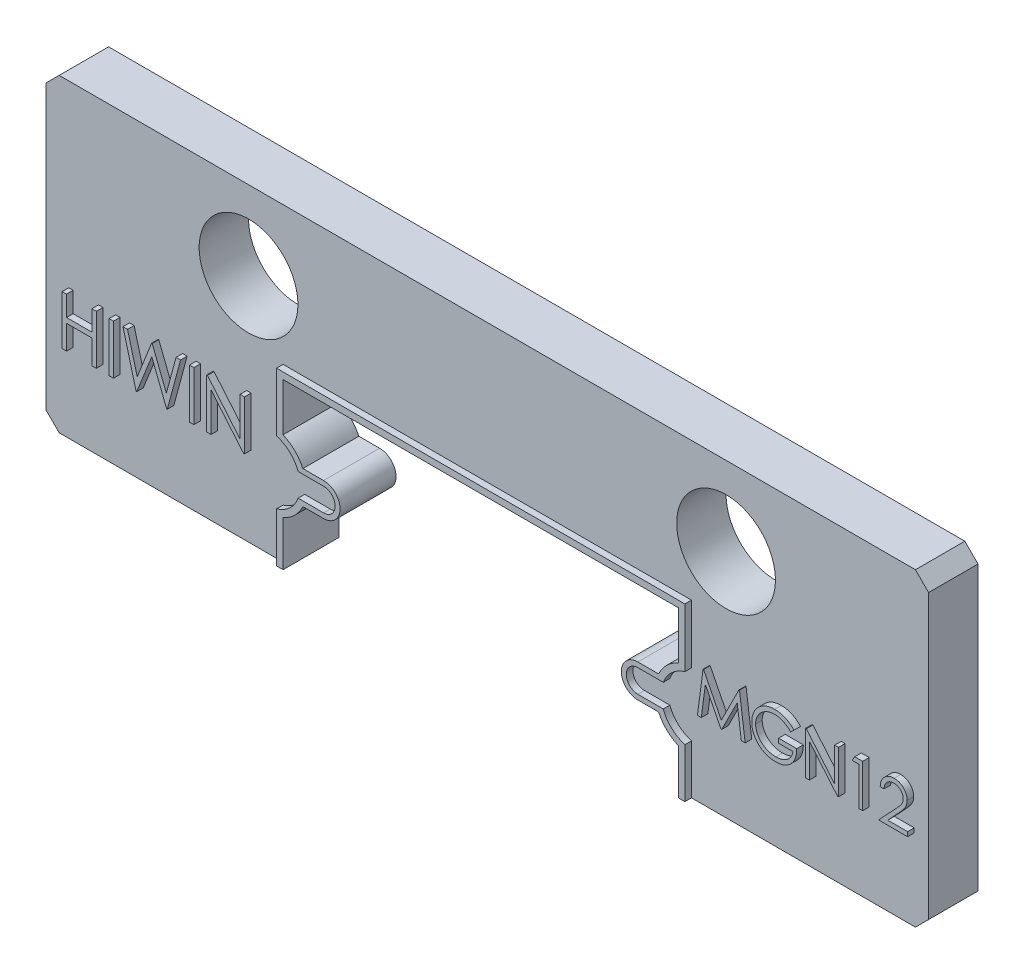
SolidWorks part; units mm, degrees
material "EPDM 60 Durometer"
ref_plane "Front Plane" through (0, 0, 0) normal (0, 0, 1) x (1, 0, 0)
ref_plane "Top Plane" through (0, 0, 0) normal (0, 1, 0) x (1, 0, 0)
ref_plane "Right Plane" through (0, 0, 0) normal (1, 0, 0) x (0, 0, -1)
sketch "Sketch1" plane through (0, 0, 0) normal (0, 0, 1) x (1, 0, 0)
  line L0 (0, 4.7) -> (0, -4.7) construction
  line L19 (-6, -4.7) -> (-13, -4.7)
  line L20 (-13, -4.7) -> (-13.4, -4.3)
  line L21 (-13.4, -4.3) -> (-13.4, 4.3)
  line L22 (-13.4, 4.3) -> (-13, 4.7)
  line L24 (-6, -4.7) -> (-6, -3.3289)
  line L25 (-6, -1.1511) -> (-6, 0.3)
  line L33 (-4.77, -2.74) -> (-5.4001, -2.74)
  line L34 (-4.77, -1.74) -> (-5.4001, -1.74)
  line L35 (-13, 4.7) -> (13, 4.7)
  line L36 (-6, 0.3) -> (6, 0.3)
  line L37 (6, -1.1511) -> (6, 0.3)
  line L38 (4.77, -1.74) -> (5.4001, -1.74)
  line L39 (4.77, -2.74) -> (5.4001, -2.74)
  line L40 (6, -4.7) -> (6, -3.3289)
  line L41 (6, -4.7) -> (13, -4.7)
  line L42 (13, -4.7) -> (13.4, -4.3)
  line L43 (13.4, -4.3) -> (13.4, 4.3)
  line L44 (13.4, 4.3) -> (13, 4.7)
  circle A6 centre (-6.48, -2.24) radius 1.19 construction
  circle A7 centre (-4.77, -2.24) radius 0.5 construction
  arc A10 (-6, -3.3289) -> (-5.4001, -2.74) centre (-6.48, -2.24) ccw
  arc A11 (-5.4001, -1.74) -> (-6, -1.1511) centre (-6.48, -2.24) ccw
  arc A12 (-4.77, -2.74) -> (-4.77, -1.74) centre (-4.77, -2.24) ccw
  arc A13 (5.4001, -1.74) -> (6, -1.1511) centre (6.48, -2.24) cw
  arc A14 (4.77, -2.74) -> (4.77, -1.74) centre (4.77, -2.24) cw
  arc A15 (6, -3.3289) -> (5.4001, -2.74) centre (6.48, -2.24) cw
  point P3 (0, 0)
  point P17 (0, 0.3)
  point P26 (0, 0.3)
  dimension "D10" = 1
  dimension "D12" = 2.54
  dimension "D8" = 9.4
  dimension "D9" = 2.38
  dimension "D11" = 2.54
  dimension "D13" = 4.77
  dimension "D14" = 6.48
  dimension "D1" = 0.4
  dimension "D2" = 0.4
  dimension "D3" = 6
  dimension "D4" = 6
  dimension "D5" = 13.4
  dimension "D6" = 0.4
  dimension "D7" = 5
extrude "Boss-Extrude1" add sketch "Sketch1" against normal blind 1.5
sketch "Sketch2" plane through (0, 0, 0) normal (0, 0, 1) x (1, 0, 0)
  line L1 (-6, -1.1511) -> (-6, 0.3) construction
  line L2 (-6, -4.7) -> (-13, -4.7) construction
  line L3 (6, -1.1511) -> (6, 0.3) construction
  line L4 (6, -4.7) -> (13, -4.7) construction
  circle A0 centre (-7.25, 2.3) radius 1.5
  circle A1 centre (7.25, 2.3) radius 1.5
  dimension "D1" = 1.25
  dimension "D2" = 7
  dimension "D3" = 1.25
  dimension "D4" = 7
extrude "Cut-Extrude1" cut sketch "Sketch2" against normal through all
sketch "Sketch3" plane through (0, 0, 0) normal (0, 0, 1) x (1, 0, 0)
  line L0 (-6.48, -2.24) -> (-13.4, -2.24) construction
  line L1 (-13.4, -4.3) -> (-13.4, 4.3) construction
  line L2 (6.48, -2.24) -> (13.4, -2.24) construction
  line L3 (13.4, -4.3) -> (13.4, 4.3) construction
  text T0 "HIWIN" font "Century Gothic" height 1.5
  text T1 "MGN12" font "Century Gothic" height 1.3
extrude "Boss-Extrude2" add sketch "Sketch3" along normal blind 0.2
sketch "Sketch4" plane through (0, 0, 0) normal (0, 0, 1) x (1, 0, 0)
  line L0 (-6.2, -4.7) -> (-6.2, -3.2)
  line L1 (-6, -4.7) -> (-13, -4.7) construction
  line L2 (-6, -4.7) -> (-6, -3.3289) construction
  line L3 (-6.2, -4.7) -> (-6, -4.7)
  line L4 (-6, -4.7) -> (-6, -3.3289)
  line L5 (-5.4001, -2.74) -> (-4.77, -2.74)
  line L6 (-4.77, -1.74) -> (-5.4001, -1.74)
  line L7 (-6, -1.1511) -> (-6, 0.3) construction
  line L8 (-6, -1.1511) -> (-6, 0.3)
  line L9 (-6.2, 0.5) -> (6.2, 0.5)
  line L10 (-6.2, 0.5) -> (-6.2, -1.28)
  line L11 (-6, 0.3) -> (6, 0.3) construction
  line L12 (6, -1.1511) -> (6, 0.3)
  line L13 (-6, 0.3) -> (6, 0.3)
  line L14 (0, 0.3) -> (0, -4.7) construction
  line L15 (-4.77, -2.59) -> (-5.5433, -2.59)
  line L16 (-4.77, -1.89) -> (-5.5433, -1.89)
  line L17 (6.2, 0.5) -> (6.2, -1.28)
  line L18 (4.77, -1.74) -> (5.4001, -1.74)
  line L19 (4.77, -1.89) -> (5.5433, -1.89)
  line L20 (4.77, -2.59) -> (5.5433, -2.59)
  line L21 (5.4001, -2.74) -> (4.77, -2.74)
  line L22 (6.2, -4.7) -> (6.2, -3.2)
  line L23 (6, -4.7) -> (6, -3.3289)
  line L24 (6.2, -4.7) -> (6, -4.7)
  circle A0 centre (-6.48, -2.24) radius 1 construction
  circle A1 centre (-4.77, -2.24) radius 0.35 construction
  arc A2 (-6, -3.3289) -> (-5.4001, -2.74) centre (-6.48, -2.24) ccw
  arc A3 (-6, -3.3289) -> (-5.4001, -2.74) centre (-6.48, -2.24) ccw construction
  arc A4 (-4.77, -2.74) -> (-4.77, -1.74) centre (-4.77, -2.24) ccw
  arc A5 (-4.77, -2.74) -> (-4.77, -1.74) centre (-4.77, -2.24) ccw construction
  arc A6 (-5.4001, -1.74) -> (-6, -1.1511) centre (-6.48, -2.24) ccw
  arc A7 (-6.2, -3.2) -> (-5.5433, -2.59) centre (-6.48, -2.24) ccw
  arc A8 (-5.5433, -1.89) -> (-6.2, -1.28) centre (-6.48, -2.24) ccw
  arc A9 (-4.77, -2.59) -> (-4.77, -1.89) centre (-4.77, -2.24) ccw
  arc A10 (5.4001, -1.74) -> (6, -1.1511) centre (6.48, -2.24) cw
  arc A11 (5.5433, -1.89) -> (6.2, -1.28) centre (6.48, -2.24) cw
  arc A12 (4.77, -2.59) -> (4.77, -1.89) centre (4.77, -2.24) cw
  arc A13 (4.77, -2.74) -> (4.77, -1.74) centre (4.77, -2.24) cw
  arc A14 (6, -3.3289) -> (5.4001, -2.74) centre (6.48, -2.24) cw
  arc A15 (6.2, -3.2) -> (5.5433, -2.59) centre (6.48, -2.24) cw
  point P51 (0, 0.5)
  dimension "D1" = 2
  dimension "D2" = 0.7
  dimension "D3" = 0.2
  dimension "D4" = 0.2
  dimension "D5" = 0.2
extrude "Boss-Extrude3" add sketch "Sketch4" along normal blind 0.2
